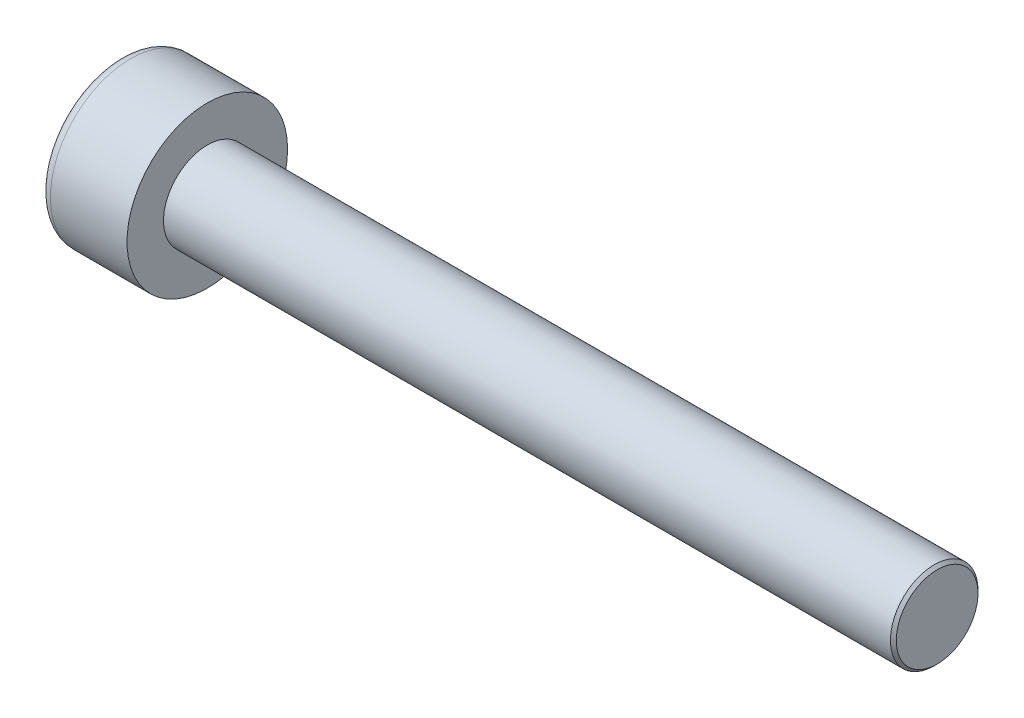
SolidWorks part; units mm, degrees
ref_plane "Front" through (0, 0, 0) normal (0, 0, 1) x (1, 0, 0)
ref_plane "Top" through (0, 0, 0) normal (0, 1, 0) x (1, 0, 0)
ref_plane "Right" through (0, 0, 0) normal (1, 0, 0) x (0, 0, -1)
sketch "Sketch1" plane through (0, 0, 0) normal (1, 0, 0) x (0, 0, -1)
  circle A0 centre (0, 0) radius 2.75
  dimension "dk" = 5.5
extrude "BaseHead" add sketch "Sketch1" along normal blind 3
sketch "Sketch2" plane through (3, 0, 0) normal (1, 0, 0) x (0, 0, -1)
  circle A0 centre (0, 0) radius 1.5
  dimension "d" = 3
extrude "BaseBody" add sketch "Sketch2" along normal blind 25
cosmetic thread "ThreadCosmetic1" parameters "b"=18, "D2"=2.459
sketch "Sketch3" plane through (0, 0, 0) normal (1, 0, 0) x (0, 0, -1)
  line L1 (1.4434, 0) -> (0.7217, 1.25)
  line L2 (0.7217, 1.25) -> (-0.7217, 1.25)
  line L3 (-0.7217, 1.25) -> (-1.4434, 0)
  line L4 (-1.4434, 0) -> (-0.7217, -1.25)
  line L5 (-0.7217, -1.25) -> (0.7217, -1.25)
  line L6 (0.7217, -1.25) -> (1.4434, 0)
  circle A0 centre (0, 0) radius 1.25 construction
  dimension "s" = 2.5
  dimension "e" = 2.8868
extrude "HexagonSocket" cut sketch "Sketch3" along normal blind 1.3
sketch "Sketch4" plane through (-4.1961, 0.75, 0) normal (0, 0, 1) x (-1, 0, 0)
  line L0 (-5.4961, 2) -> (-6.2178, 0.75)
  line L2 (-6.2178, 0.75) -> (-5.4961, 0.75)
  line L3 (-5.4961, 0.75) -> (-5.4961, 2)
  line L4 (-5.0351, 0.75) -> (0.839, 0.75) construction
  line L5 (-32.1961, 0.75) -> (-7.1961, 0.75) construction
  line L6 (-7.1961, 0.75) -> (-4.1961, 0.75) construction
  dimension "m" = 60
revolve "Cut-Revolve1" cut sketch "Sketch4" angle 360 about L4
fillet "HeadFillet" [suppressed] radius 0.1
fillet "TopFillet" radius 0.375 1 edges at (0, 0, -2.75)
chamfer "Chamfer1" distance 0.1 angle 45 1 edges at (28, 0, -1.5)
sketch "Sketch5" plane through (0, 0, 0) normal (0, 0, 1) x (1, 0, 0)
  line L0 (27.9, 1.2657) -> (28.0353, 1.5)
  line L1 (28.0353, 1.5) -> (28.0353, 1.7705)
  line L2 (28.0353, 1.7705) -> (27.7648, 1.7705)
  line L3 (27.7648, 1.7705) -> (27.7648, 1.5)
  line L4 (27.7648, 1.5) -> (27.9, 1.2657)
  line L5 (0, 0) -> (7.8886, 0) construction
  line L6 (27.9, -1.5) -> (27.9, 1.5) construction
  dimension "D1" = 3
  dimension "D2" = 0.2705
revolve "Cut-Revolve10" [suppressed] cut sketch "Sketch5" angle 360 about L5
pattern_linear "LPattern10" [suppressed] count 55 spacing 0.3246 along (1, 0, 0)
equation "\"r1@TopFillet\" = \"d@Sketch2\" / 8"
equation "\"D1@Chamfer1\" = \"r@HeadFillet\""
equation "\"D1@Sketch5\" = \"d@Sketch2\""
equation "\"D2@Sketch5\" =  ( \"d@Sketch2\" - \"D2@ThreadCosmetic1\" )  / 2"
equation "\"D3@LPattern10\" = \"D2@Sketch5\" * 1.2"
equation "\"D1@LPattern10\" = \"b@ThreadCosmetic1\" / \"D3@LPattern10\""
